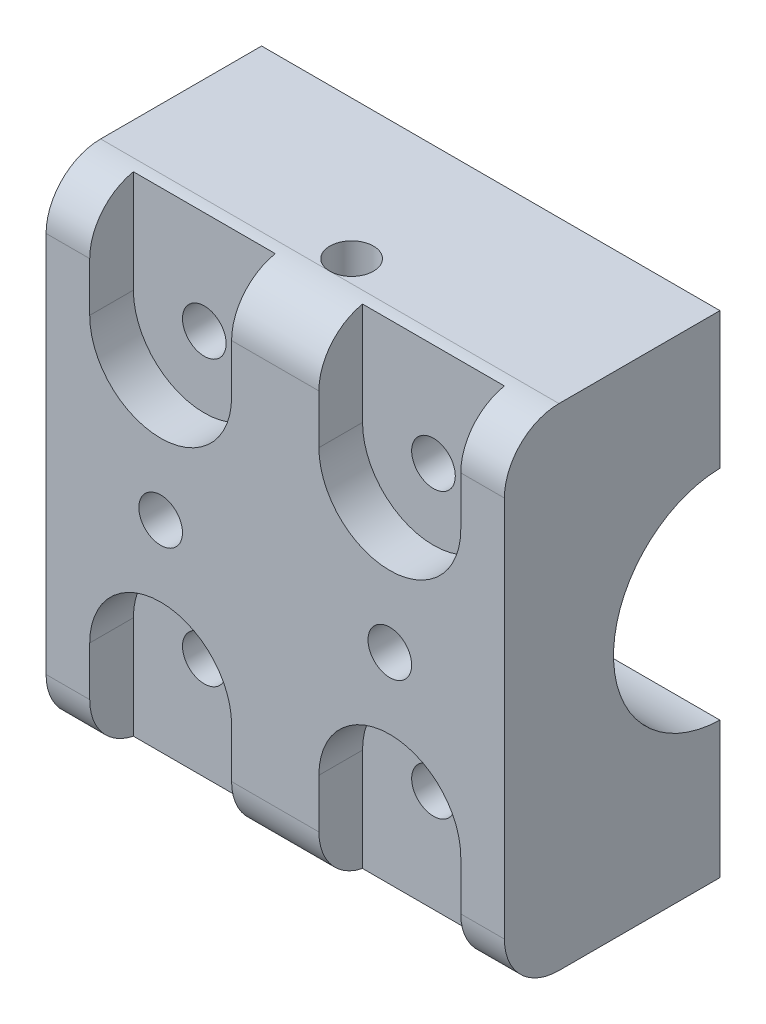
SolidWorks part; units mm, degrees
ref_plane "Front Plane" through (0, 0, 0) normal (0, 0, 1) x (1, 0, 0)
ref_plane "Top Plane" through (0, 0, 0) normal (0, 1, 0) x (1, 0, 0)
ref_plane "Right Plane" through (0, 0, 0) normal (1, 0, 0) x (0, 0, -1)
sketch "Sketch1" plane through (0, 0, 0) normal (1, 0, 0) x (0, 0, -1)
  line L0 (0, 22.5) -> (0, -22.5) construction
  line L1 (-0.25, 22.5) -> (-0.25, 9.9969)
  line L2 (-0.25, -9.9969) -> (-0.25, -22.5)
  line L4 (-0.25, 22.5) -> (-0.25, -22.5) construction
  line L6 (-20, 17.5) -> (-20, -17.5)
  line L8 (0, 22.5) -> (-15, 22.5)
  line L10 (0, 0) -> (-20, 0) construction
  line L12 (0, -22.5) -> (-15, -22.5)
  arc A1 (0, 10) -> (0, -10) centre (0, 0) ccw
  circle A3 centre (0, 0) radius 10 construction
  arc A4 (-15, 22.5) -> (-20, 17.5) centre (-15, 17.5) ccw
  arc A5 (-20, -17.5) -> (-15, -22.5) centre (-15, -17.5) ccw
  point P23 (-10, 0)
  dimension "D2" = 45
  dimension "D4" = 5
  dimension "D3" = 20
  dimension "D1" = 0.25
extrude "Boss-Extrude1" add sketch "Sketch1" against normal blind 42
sketch "Sketch2" plane through (0, 0, 0.25) normal (0, 0, 1) x (1, 0, 0)
  line L0 (0, 0) -> (-42, 0) construction
  line L2 (-42, 13) -> (-21, 13) construction
  line L3 (-10.5, 11) -> (-31.5, 11) construction
  line L4 (-42, 22.5) -> (0, 22.5) construction
  line L5 (-21, 22.5) -> (-21, -22.5) construction
  line L7 (-42, 17.5) -> (-42, -17.5) construction
  line L8 (-42, 17.5) -> (-42, -17.5) construction
  line L9 (-42, -22.5) -> (0, -22.5) construction
  circle A0 centre (-31.5, 13) radius 2
  circle A1 centre (-10.5, 13) radius 2
  circle A2 centre (-10.5, -13) radius 2
  circle A3 centre (-31.5, -13) radius 2
  point P21 (-21, 11)
  dimension "D2" = 4
  dimension "D1" = 13
extrude "Cut-Extrude2" cut sketch "Sketch2" along normal through all contours A1 | A0 | A3 | A2
sketch "Sketch3" plane through (0, 0, 20) normal (0, 0, 1) x (1, 0, 0)
  line L0 (0, 0) -> (-42, 0) construction
  line L1 (-42, 22.5) -> (0, 22.5) construction
  line L2 (-38, 13) -> (-38, 22.5)
  line L3 (-38, 22.5) -> (-25, 22.5)
  line L4 (-25, 22.5) -> (-25, 13)
  line L5 (-17, 13) -> (-17, 22.5)
  line L6 (-17, 22.5) -> (-4, 22.5)
  line L7 (-4, 22.5) -> (-4, 13)
  line L8 (-4, -22.5) -> (-4, -13)
  line L9 (-17, -22.5) -> (-4, -22.5)
  line L10 (-17, -13) -> (-17, -22.5)
  line L11 (-25, -22.5) -> (-25, -13)
  line L12 (-38, -22.5) -> (-25, -22.5)
  line L13 (-38, -13) -> (-38, -22.5)
  line L14 (-42, 17.5) -> (-42, -17.5) construction
  arc A0 (-38, 13) -> (-25, 13) centre (-31.5, 13) ccw
  arc A1 (-17, 13) -> (-4, 13) centre (-10.5, 13) ccw
  arc A2 (-17, -13) -> (-4, -13) centre (-10.5, -13) cw
  arc A3 (-38, -13) -> (-25, -13) centre (-31.5, -13) cw
  dimension "D1" = 13
extrude "Cut-Extrude3" cut sketch "Sketch3" against normal blind 4
sketch "Sketch4" plane through (0, 0, 20) normal (0, 0, 1) x (1, 0, 0)
  circle A0 centre (-10.5, 0) radius 2
  circle A1 centre (-31.5, 0) radius 2
  circle A2 centre (-10.5, 0) radius 2 construction
extrude "Cut-Extrude4" cut sketch "Sketch4" against normal through all
sketch "Sketch5" plane through (0, -22.5, 0) normal (0, -1, 0) x (1, 0, 0)
  line L0 (-21, 20) -> (-21, 0.25) construction
  line L3 (-25, 20) -> (-17, 20) construction
  line L4 (-42, 0.25) -> (0, 0.25) construction
  line L5 (-42, 15) -> (0, 15) construction
  circle A0 centre (-21, 13) radius 2
  dimension "D1" = 4
extrude "Cut-Extrude5" cut sketch "Sketch5" against normal through all
